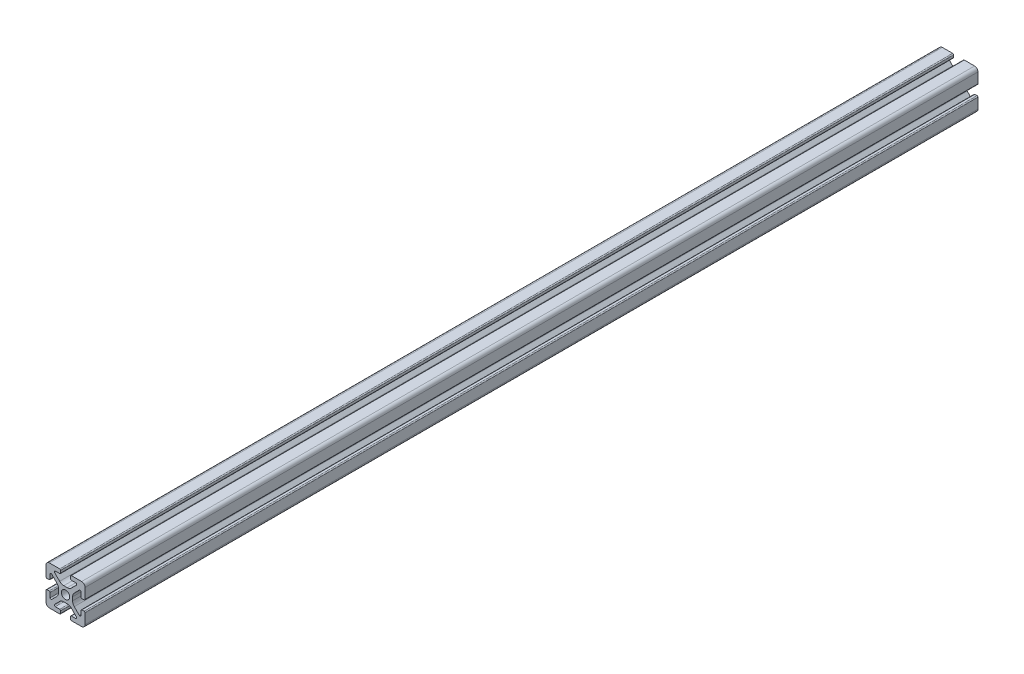
SolidWorks part; units mm, degrees
ref_plane "Front Plane" through (0, 0, 0) normal (0, 0, 1) x (1, 0, 0)
ref_plane "Top Plane" through (0, 0, 0) normal (0, 1, 0) x (1, 0, 0)
ref_plane "Right Plane" through (0, 0, 0) normal (1, 0, 0) x (0, 0, -1)
sketch "Sketch2" plane through (0, 0, 0) normal (0, 0, 1) x (1, 0, 0)
  line L0 (0, 10) -> (0, -10) construction
  line L1 (-10, 0) -> (10, 0) construction
  line L2 (2.5, -10) -> (10, -10)
  line L3 (10, -10) -> (10, -2.5)
  line L4 (2.5, -10) -> (2.5, -7.9246)
  line L5 (2.5, -7.9246) -> (6.4571, -7.9246)
  line L6 (6.4571, -7.9246) -> (2.1325, -3.6)
  line L7 (0, 0) -> (10, -10) construction
  line L8 (10, -2.5) -> (7.9246, -2.5)
  line L9 (7.9246, -2.5) -> (7.9246, -6.4571)
  line L10 (7.9246, -6.4571) -> (3.6, -2.1325)
  line L11 (5.7623, -4.2948) -> (4.2948, -5.7623) construction
  circle A0 centre (0, 0) radius 2.15
  arc A1 (5.25, -7.9246) -> (5.6036, -7.0711) centre (5.25, -7.4246) ccw construction
  point P8 (0, -3.6)
  point P16 (5.0286, -5.0286)
  dimension "Center Hole Diameter" = 4.3
  dimension "D3" = 0.5
  dimension "Rail Height" = 20
  dimension "Rail Width" = 20
  dimension "T-Slot Width" = 5
  dimension "Slot Depth" = 6.4
  dimension "Slot Inner Width" = 11.5
sketch "Sketch3" plane through (0, 0, 0) normal (1, 0, 0) x (0, 0, -1)
  line L0 (-228.6, -10) -> (228.6, -10) construction
  line L1 (-203.2, 0) -> (203.2, 0) construction
  line L2 (0, 10) -> (0, -10) construction
  line L3 (0, 10) -> (0, -10) construction
  point P6 (-203.2, 0)
  point P8 (203.2, 0)
  dimension "Length" = 457.2
  dimension "D1" = 25.4
sketch "Sketch4" plane through (0, 0, 0) normal (0, 0, 1) x (1, 0, 0)
  line L0 (3, -10) -> (8.25, -10)
  line L1 (2.5, -10) -> (10, -10) construction
  line L2 (2.5, -10) -> (2.5, -7.9246) construction
  line L3 (2.5, -7.9246) -> (6.4571, -7.9246) construction
  line L4 (2.5, -8.4246) -> (2.5, -9.5)
  line L5 (3, -7.9246) -> (5.25, -7.9246)
  line L6 (0, -3.6) -> (0.8898, -3.6)
  line L7 (6.4571, -7.9246) -> (2.1325, -3.6) construction
  line L8 (3.0112, -4.4787) -> (5.6036, -7.0711)
  line L9 (10, -10) -> (10, -2.5) construction
  line L10 (7.9246, -6.4571) -> (3.6, -2.1325) construction
  line L11 (7.9246, -2.5) -> (7.9246, -6.4571) construction
  line L12 (7.9246, -5.25) -> (7.9246, -3)
  line L13 (10, -2.5) -> (7.9246, -2.5) construction
  line L14 (8.4246, -2.5) -> (9.5, -2.5)
  line L15 (10, -3) -> (10, -8.25)
  line L16 (7.0711, -5.6036) -> (4.4787, -3.0112)
  line L17 (3.6, 0) -> (3.6, -0.8898)
  line L18 (-10, 0) -> (10, 0) construction
  line L19 (0, -3.6) -> (0, -2.15)
  line L20 (0, 10) -> (0, -10) construction
  line L21 (3.6, 0) -> (2.15, 0)
  arc A0 (2.5, -9.5) -> (3, -10) centre (3, -9.5) ccw
  arc A1 (5.25, -7.9246) -> (5.6036, -7.0711) centre (5.25, -7.4246) ccw construction
  arc A2 (2.5, -8.4246) -> (3, -7.9246) centre (3, -8.4246) cw
  arc A3 (5.25, -7.9246) -> (5.6036, -7.0711) centre (5.25, -7.4246) ccw
  arc A4 (0.8898, -3.6) -> (3.0112, -4.4787) centre (0.8898, -6.6) cw
  arc A5 (8.25, -10) -> (10, -8.25) centre (8.25, -8.25) ccw
  arc A6 (7.0711, -5.6036) -> (7.9246, -5.25) centre (7.4246, -5.25) ccw
  arc A7 (7.9246, -3) -> (8.4246, -2.5) centre (8.4246, -3) cw
  arc A8 (9.5, -2.5) -> (10, -3) centre (9.5, -3) cw
  arc A9 (4.4787, -3.0112) -> (3.6, -0.8898) centre (6.6, -0.8898) cw
  circle A10 centre (0, 0) radius 2.15 construction
  arc A11 (0, -2.15) -> (2.15, 0) centre (0, 0) ccw
  dimension "D1" = 1.75
  dimension "D2" = 3
extrude "Boss-Extrude1" add sketch "Sketch4" along normal mid plane 457.2
mirror "Mirror1" about plane through (0, 0, 0) normal (1, 0, 0) of bodies 134
mirror "Mirror2" about plane through (0, 0, 0) normal (0, 1, 0) of bodies 135
equation "\"D3@Sketch2\"=\"T-Slot Width@Sketch2\"*0.1"
equation "\"D1@Sketch4\"=\"D3@Sketch2\"*3.5"
equation "\"D2@Sketch4\"=\"D3@Sketch2\"*6"
equation "\"D1@Boss-Extrude1\"=\"Length@Sketch3\""
